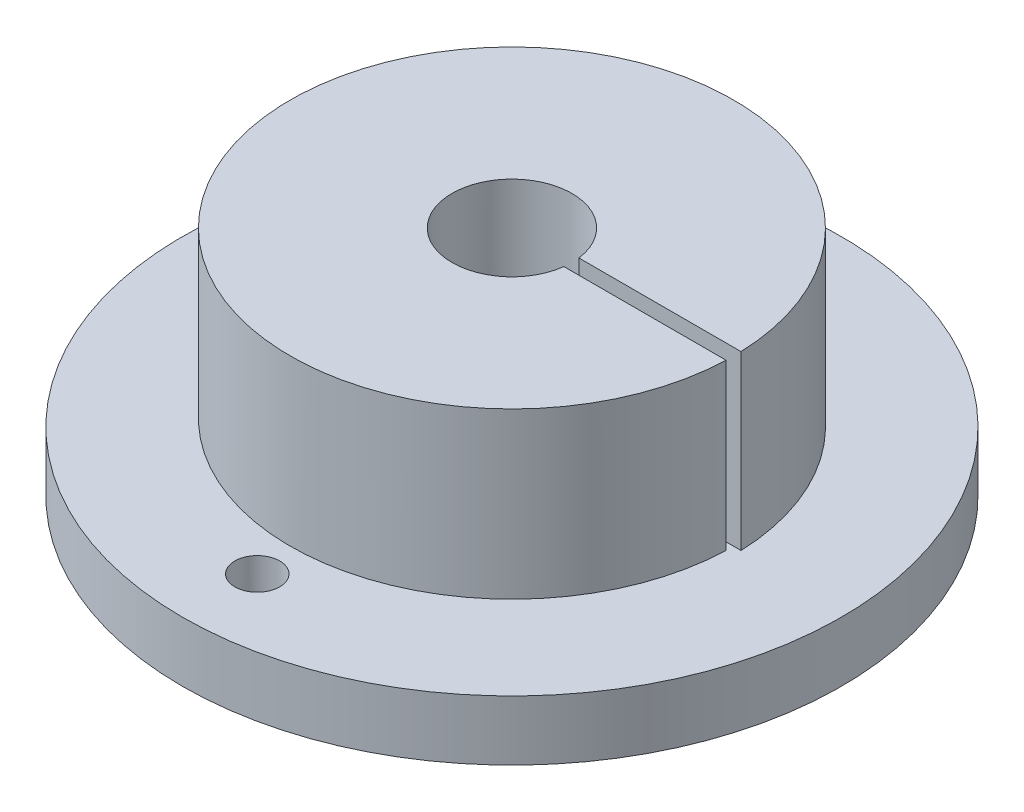
SolidWorks part; units mm, degrees
ref_plane "前视基准面" through (0, 0, 0) normal (0, 0, 1) x (1, 0, 0)
ref_plane "上视基准面" through (0, 0, 0) normal (0, 1, 0) x (1, 0, 0)
ref_plane "右视基准面" through (0, 0, 0) normal (1, 0, 0) x (0, 0, -1)
sketch "草图1" plane through (0, 0, 0) normal (0, 1, 0) x (1, 0, 0)
  circle A0 centre (0, 0) radius 22
extrude "凸台-拉伸1" add sketch "草图1" along normal blind 4
sketch "草图2" plane through (0, 4, 0) normal (0, 1, 0) x (1, 0, 0)
  circle A0 centre (0, 0) radius 14.8
extrude "凸台-拉伸2" add sketch "草图2" along normal blind 11.5
sketch "草图3" plane through (0, 15.5, 0) normal (0, 1, 0) x (1, 0, 0)
  circle A0 centre (0, 0) radius 4
extrude "切除-拉伸1" cut sketch "草图3" against normal through all
sketch "草图4" plane through (0, 0, 0) normal (0, -1, 0) x (1, 0, 0)
  circle A0 centre (0, 0) radius 17
  circle A1 centre (0, 17) radius 1.5
  circle A2 centre (0, -17) radius 1.5
extrude "切除-拉伸2" cut sketch "草图4" against normal through all contours A1 | A2
sketch "草图5" plane through (0, 0, 0) normal (1, 0, 0) x (0, 0, -1)
  line L0 (0, 4) -> (0, 4.5)
  line L1 (22, 4) -> (-22, 4) construction
  line L2 (0, 4.5) -> (-14.8, 4.5)
  line L3 (-14.8, 15.5) -> (-14.8, 4) construction
  line L4 (-14.8, 4.5) -> (-14.8, 4)
  line L5 (-14.8, 15.5) -> (-14.8, 4) construction
  line L6 (-14.8, 4) -> (0, 4)
  dimension "D1" = 0.5
extrude "切除-拉伸3" cut sketch "草图5" against normal mid plane 30
sketch "草图6" plane through (0, 15.5, 0) normal (0, 1, 0) x (1, 0, 0)
  line L0 (0, 0) -> (0, 0.5)
  line L1 (0, 0.5) -> (16.9941, 0.5)
  line L2 (16.9941, 0.5) -> (16.9941, -0.5)
  line L3 (16.9941, -0.5) -> (0, -0.5)
  line L4 (0, -0.5) -> (0, 0)
  dimension "D1" = 0.5
  dimension "D2" = 0.5
extrude "切除-拉伸4" cut sketch "草图6" against normal blind 11.5
